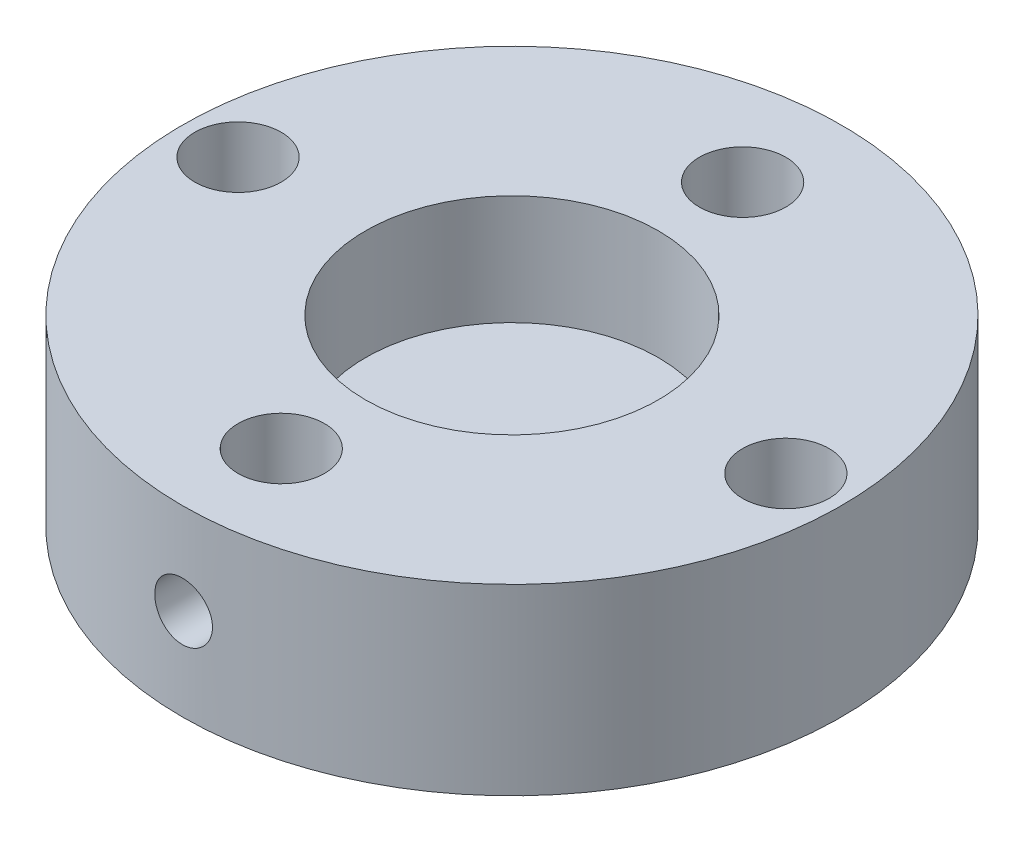
SolidWorks part; units mm, degrees
ref_plane "Front Plane" through (0, 0, 0) normal (0, 0, 1) x (1, 0, 0)
ref_plane "Top Plane" through (0, 0, 0) normal (0, 1, 0) x (1, 0, 0)
ref_plane "Right Plane" through (0, 0, 0) normal (1, 0, 0) x (0, 0, -1)
sketch "Sketch2" plane through (0, 0, 0) normal (0, 1, 0) x (1, 0, 0)
  circle A0 centre (0, 0) radius 11.43
  dimension "D1" = 22.86
extrude "Boss-Extrude1" add sketch "Sketch2" along normal blind 6.35
sketch "Sketch4" plane through (0, 6.35, 0) normal (0, 1, 0) x (1, 0, 0)
  line L0 (0, 9.5) -> (0, -9.5)
  line L1 (-9.5, 0) -> (9.5, 0)
  circle A0 centre (0, 0) radius 9.5
  circle A1 centre (0, 0) radius 8
  circle A2 centre (0, 8) radius 1.5
  circle A3 centre (0, -8) radius 1.5
  circle A4 centre (9.5, 0) radius 1.5
  circle A5 centre (-9.5, 0) radius 1.5
  dimension "D1" = 19
  dimension "D2" = 16
  dimension "D3" = 3
extrude "Cut-Extrude1" cut sketch "Sketch4" against normal through all contours A0 A5 | A0 A5 L1 | L1 A5 A0 | A1 A2 L0 | L0 A2 A1 | A1 A2 L0 | L0 A2 A1 | A0 A4 | L0 A3 A1 | A1 A3 L0 | L0 A3 A1 | A1 A3 L0 | A0 A4 L1 | L1 A4 A0
ref_plane "Plane1" through (0, 0, 12.7) normal (0, 0, 1) x (1, 0, 0)
sketch "Sketch8" plane through (0, 0, 12.7) normal (0, 0, 1) x (1, 0, 0)
  line L0 (0, 6.35) -> (0, 0)
  line L1 (11.43, 6.35) -> (-11.43, 6.35) construction
  circle A0 centre (0, 3.175) radius 1
  dimension "D1" = 2
extrude "Cut-Extrude2" cut sketch "Sketch8" against normal offset from surface (4.3295 mm away) 3 contours L0 A0 | L0 A0
ref_plane "Plane2" through (0, 0, -12.7) normal (0, 0, 1) x (1, 0, 0)
sketch "Sketch9" plane through (0, 0, -12.7) normal (0, 0, 1) x (1, 0, 0)
  circle A0 centre (0, 3.175) radius 1
extrude "Cut-Extrude3" cut sketch "Sketch9" along normal offset from surface (4.3295 mm away) 3
sketch "Sketch10" plane through (0, 6.35, 0) normal (0, 1, 0) x (1, 0, 0)
  circle A0 centre (0, 0) radius 5.08
  dimension "D1" = 10.16
extrude "Cut-Extrude4" cut sketch "Sketch10" against normal blind 3.81
